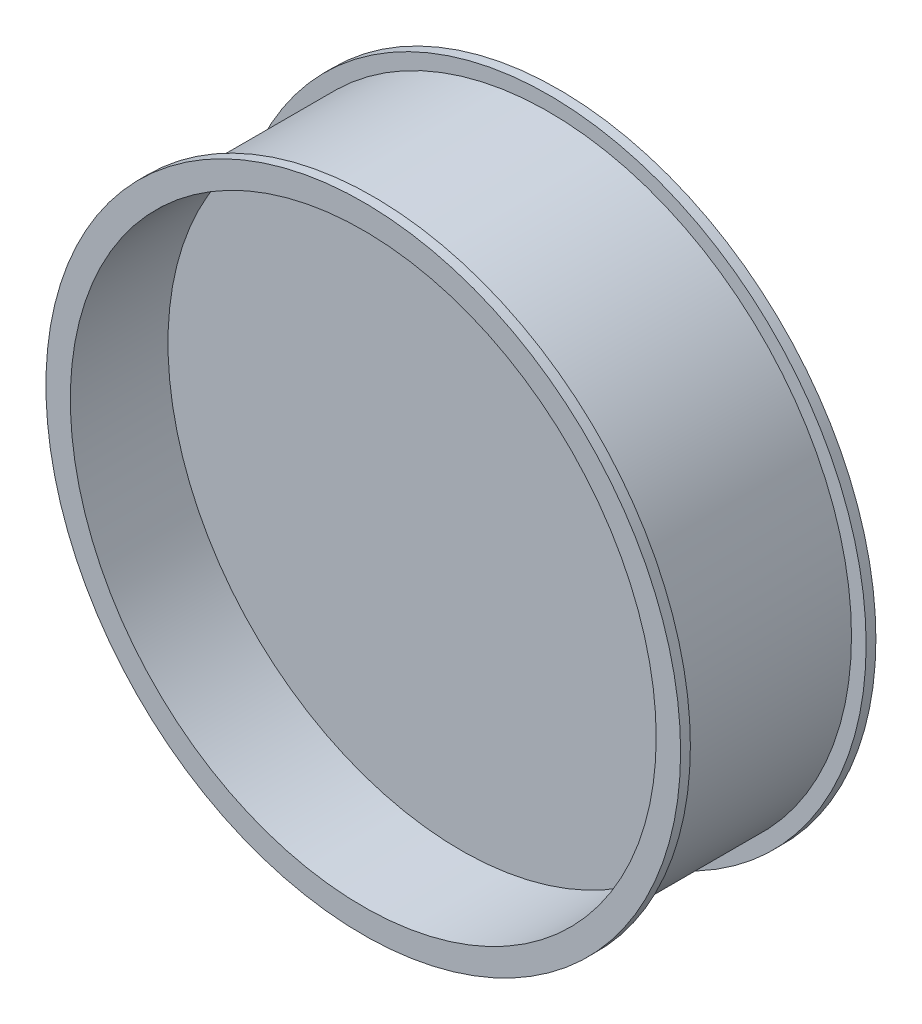
SolidWorks part; units mm, degrees
ref_plane "Plan de face" through (0, 0, 0) normal (0, 0, 1) x (1, 0, 0)
ref_plane "Plan de dessus" through (0, 0, 0) normal (0, 1, 0) x (1, 0, 0)
ref_plane "Plan de droite" through (0, 0, 0) normal (1, 0, 0) x (0, 0, -1)
sketch "Esquisse1" plane through (0, 0, 0) normal (0, 0, 1) x (1, 0, 0)
  circle A0 centre (0, 0) radius 32.5
  dimension "D1" = 65
extrude "Boss.-Extru.1" add sketch "Esquisse1" along normal blind 1
sketch "Esquisse2" plane through (0, 0, 1) normal (0, 0, 1) x (1, 0, 0)
  circle A0 centre (0, 0) radius 31
  dimension "D1" = 62
extrude "Boss.-Extru.2" add sketch "Esquisse2" along normal blind 18
sketch "Esquisse3" plane through (0, 0, 19) normal (0, 0, 1) x (1, 0, 0)
  circle A0 centre (0, 0) radius 32.5
  dimension "D1" = 65
extrude "Boss.-Extru.3" add sketch "Esquisse3" along normal blind 1
sketch "Esquisse4" plane through (0, 0, 20) normal (0, 0, 1) x (1, 0, 0)
  circle A0 centre (0, 0) radius 30
  dimension "D1" = 60
extrude "Enlèv. mat.-Extru.1" cut sketch "Esquisse4" against normal blind 10
